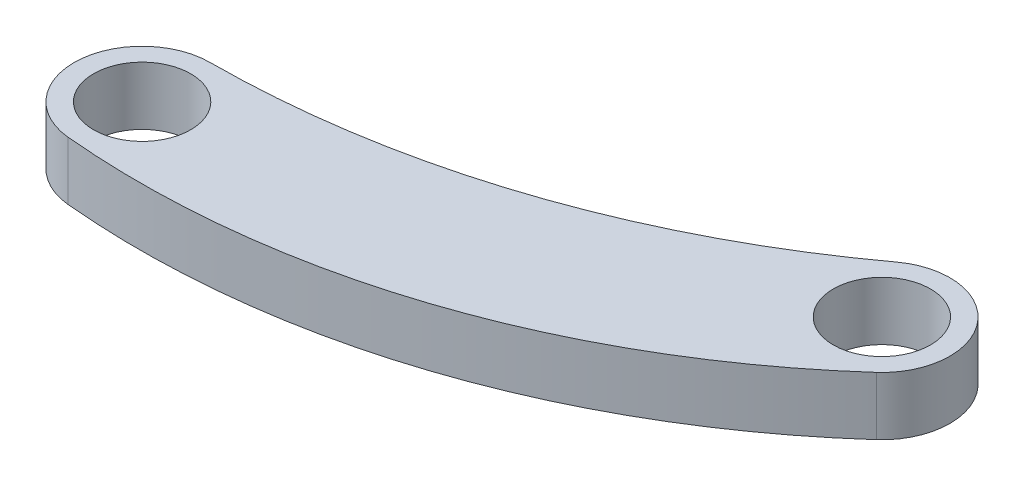
SolidWorks part; units mm, degrees
ref_plane "前视基准面" through (0, 0, 0) normal (0, 0, 1) x (1, 0, 0)
ref_plane "上视基准面" through (0, 0, 0) normal (0, 1, 0) x (1, 0, 0)
ref_plane "右视基准面" through (0, 0, 0) normal (1, 0, 0) x (0, 0, -1)
sketch "草图1" plane through (0, 0, 0) normal (0, 1, 0) x (1, 0, 0)
  arc A2 (6.7962, -80.104) -> (6.4796, -87.0887) centre (6.8058, -83.604) ccw
  arc A3 (37.7668, -76.7652) -> (33.3556, -71.3405) centre (35.4308, -74.1588) ccw
  arc A4 (6.7962, -80.104) -> (33.3556, -71.3405) centre (6.6736, -35.1041) ccw
  arc A5 (6.4796, -87.0887) -> (37.7668, -76.7652) centre (10.3128, -46.1335) ccw
  dimension "D1" = 45
  dimension "D4" = 7
  dimension "D5" = 7
extrude "凸台-拉伸1" add sketch "草图1" along normal blind 3
sketch "草图2" plane through (0, 0, 0) normal (0, 1, 0) x (1, 0, 0)
  circle A0 centre (6.8058, -83.604) radius 2.5
  circle A1 centre (35.4308, -74.1588) radius 2.5
extrude "切除-拉伸1" cut sketch "草图2" along normal blind 3
